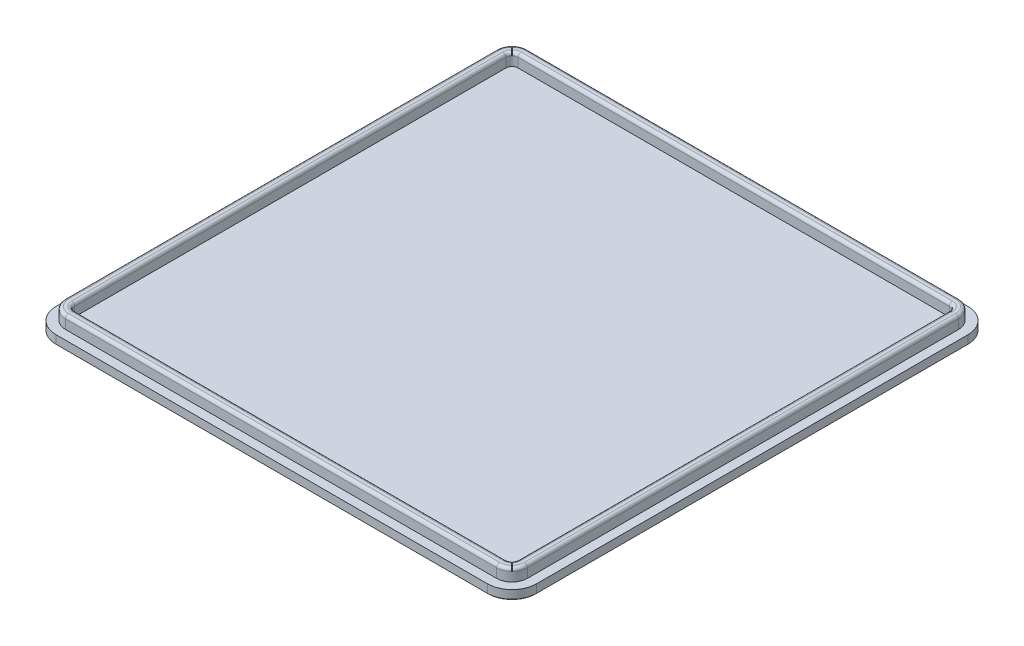
SolidWorks part; units mm, degrees
ref_plane "Front Plane" through (0, 0, 0) normal (0, 0, 1) x (1, 0, 0)
ref_plane "Top Plane" through (0, 0, 0) normal (0, 1, 0) x (1, 0, 0)
ref_plane "Right Plane" through (0, 0, 0) normal (1, 0, 0) x (0, 0, -1)
sketch "Sketch1" plane through (0, 0, 0) normal (0, 1, 0) x (1, 0, 0)
  line L1 (-70, 78) -> (70, 78)
  line L2 (-78, 70) -> (-78, -70)
  line L3 (-70, -78) -> (70, -78)
  line L4 (78, 70) -> (78, -70)
  line L5 (-78, 78) -> (78, -78) construction
  line L6 (-78, -78) -> (78, 78) construction
  arc A0 (78, 70) -> (70, 78) centre (70, 70) ccw
  arc A1 (78, -70) -> (70, -78) centre (70, -70) cw
  arc A2 (-78, -70) -> (-70, -78) centre (-70, -70) ccw
  arc A3 (-78, 70) -> (-70, 78) centre (-70, 70) cw
  point P0 (0, 0)
  dimension "D3" = 8
  dimension "D1" = 140
  dimension "D2" = 140
extrude "Boss-Extrude1" add sketch "Sketch1" along normal blind 3
sketch "Sketch2" plane through (0, 3, 0) normal (0, 1, 0) x (1, 0, 0)
  line L1 (-70, 75) -> (70, 75)
  line L2 (-75, 70) -> (-75, -70)
  line L3 (-70, -75) -> (70, -75)
  line L4 (75, 70) -> (75, -70)
  line L5 (-75, 75) -> (75, -75) construction
  line L6 (-75, -75) -> (75, 75) construction
  arc A0 (-70, -75) -> (-75, -70) centre (-70, -70) cw
  arc A1 (70, -75) -> (75, -70) centre (70, -70) ccw
  arc A2 (75, 70) -> (70, 75) centre (70, 70) ccw
  arc A3 (-70, 75) -> (-75, 70) centre (-70, 70) ccw
  point P0 (0, 0)
  dimension "D3" = 5
  dimension "D1" = 150
  dimension "D2" = 150
extrude "Extrude-Thin1" add sketch "Sketch2" along normal blind 4 thin
fillet "Fillet1" radius 1 16 edges at (71.4142, 7, 71.4142) (72, 7, 0) (71.4142, 7, -71.4142) (0, 7, -72) (-71.4142, 7, -71.4142) (-72, 7, 0) (-71.4142, 7, 71.4142) (0, 7, 72) (-75, 7, 0) (-73.5355, 7, -73.5355) (0, 7, -75) (73.5355, 7, -73.5355) (75, 7, 0) (73.5355, 7, 73.5355) (0, 7, 75) (-73.5355, 7, 73.5355)
sketch "Sketch3" plane through (0, 7, 0) normal (0, 1, 0) x (1, 0, 0)
  line L0 (-75, 70) -> (-75, 75) construction
  line L1 (-70, 75) -> (-75, 75) construction
  line L2 (-75.0707, 74.9293) -> (-74.9293, 75.0707) construction
  line L3 (-75.0707, 74.9293) -> (78.5176, -78.659)
  line L4 (78.5176, -78.659) -> (78.659, -78.5176)
  line L5 (78.659, -78.5176) -> (-74.9293, 75.0707)
  line L6 (-74.9293, 75.0707) -> (-75.0707, 74.9293)
  arc A0 (-70, 75) -> (-75, 70) centre (-70, 70) ccw construction
  point P10 (-75, 75)
extrude "Cut-Extrude1" cut sketch "Sketch3" against normal blind 3.8 draft 2.5
chamfer "Chamfer1" distance 0.3 angle 45 8 edges at (0, 0, -78) (-75.6569, 0, -75.6569) (-78, 0, 0) (-75.6569, 0, 75.6569) (0, 0, 78) (75.6569, 0, 75.6569) (78, 0, 0) (75.6569, 0, -75.6569)
